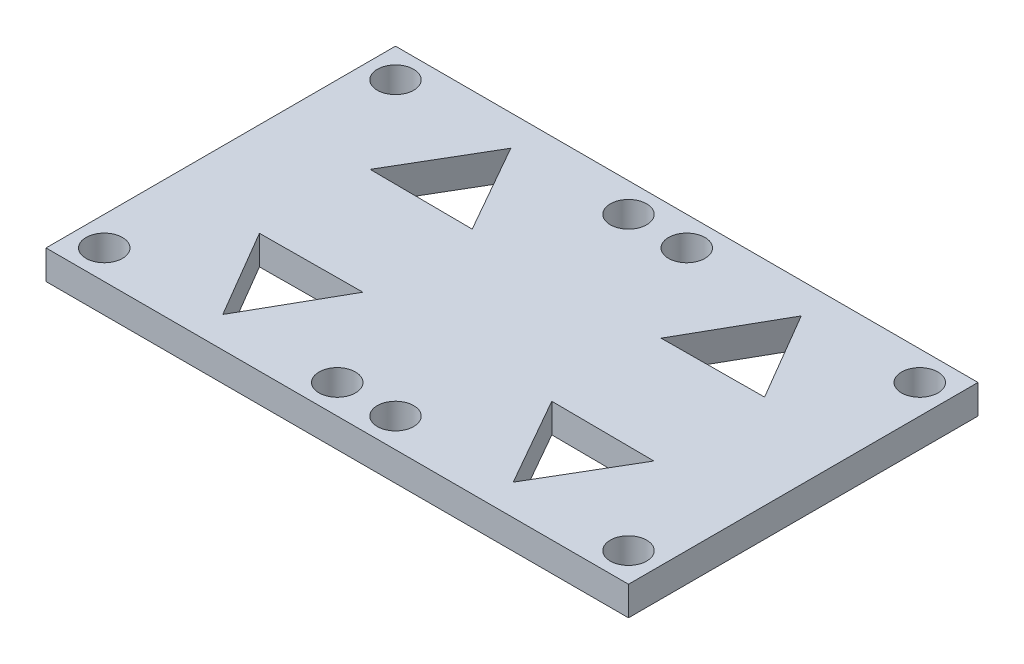
SolidWorks part; units mm, degrees
ref_plane "Front Plane" through (0, 0, 0) normal (0, 0, 1) x (1, 0, 0)
ref_plane "Top Plane" through (0, 0, 0) normal (0, 1, 0) x (1, 0, 0)
ref_plane "Right Plane" through (0, 0, 0) normal (1, 0, 0) x (0, 0, -1)
sketch "Sketch1" plane through (0, 0, 0) normal (0, 1, 0) x (1, 0, 0)
  line L0 (0, 152.4) -> (0, 0) construction
  line L1 (0, 152.4) -> (127, 152.4)
  line L4 (127, 152.4) -> (127, 0)
  line L6 (101.6, 127) -> (101.6, 0) construction
  line L9 (0, 152.4) -> (0, 0)
  line L10 (0, 0) -> (127, 0)
  line L11 (-127, 152.4) -> (127, 152.4) construction
  line L13 (-101.6, 127) -> (101.6, 127) construction
  line L15 (-101.6, 25.4) -> (101.6, 25.4) construction
  line L16 (-127, 0) -> (127, 0) construction
  line L18 (101.6, 127) -> (101.6, 25.4) construction
  line L19 (127, 152.4) -> (127, 0) construction
  line L20 (-101.6, 127) -> (-101.6, 25.4) construction
  line L21 (-127, 152.4) -> (-127, 0) construction
  circle A1 centre (101.6, 127) radius 15.875
  point P6 (0, 0)
  dimension "D3" = 25.4
  dimension "D4" = 31.75
  dimension "D1" = 152.4
  dimension "D2" = 127
extrude "Boss-Extrude1" add sketch "Sketch1" along normal blind 25.4
mirror "Mirror1" about plane through (0, 25.4, 0) normal (0, 0, -1) of "Boss-Extrude1"
mirror "Mirror2" about plane through (0, 25.4, -152.4) normal (1, 0, 0) of bodies 102
sketch "Sketch2" plane through (0, 25.4, 0) normal (0, 1, 0) x (1, 0, 0)
  line L1 (44.6427, 47.6475) -> (0.3552, 125.5862)
  line L2 (0.3552, 125.5862) -> (-44.9979, 48.2628)
  line L3 (-44.9979, 48.2628) -> (44.6427, 47.6475)
  circle A0 centre (0, 73.8322) radius 25.8776 construction
extrude "Cut-Extrude1" cut sketch "Sketch2" against normal blind 25.4
mirror "Mirror3" about plane through (0, 0, 0) normal (0, 0, 1) of "Cut-Extrude1"
mirror "Mirror4" about plane through (127, 25.4, -152.4) normal (-1, 0, 0) of bodies 105
